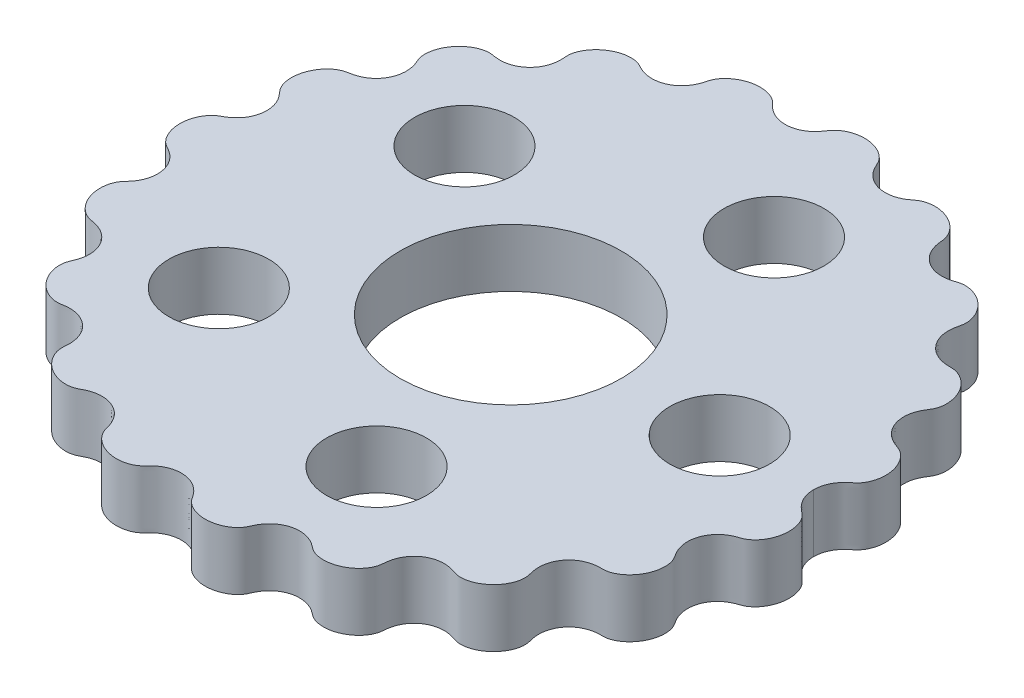
SolidWorks part; units mm, degrees
ref_plane "Front Plane" through (0, 0, 0) normal (0, 0, 1) x (1, 0, 0)
ref_plane "Top Plane" through (0, 0, 0) normal (0, 1, 0) x (1, 0, 0)
ref_plane "Right Plane" through (0, 0, 0) normal (1, 0, 0) x (0, 0, -1)
sketch "Sketch1" plane through (0, 0, 0) normal (0, 1, 0) x (1, 0, 0)
  line L0 (-28.5, 0) -> (26.1, 0) construction
  line L1 (0, 0) -> (-1.2, 0) construction
  line L2 (-1.2, -26.2965) -> (-1.2, 26.2965) construction
  line L3 (0, -27.4748) -> (0, 27.4748) construction
  line L4 (18, 0) -> (16.8, 0)
  line L5 (-1.2, 0) -> (-2.4, 0)
  circle A6 centre (0, 0) radius 9.525
  circle A7 centre (0, 0) radius 18
  circle A8 centre (18, 0) radius 4.3
  circle A9 centre (5.5623, -17.119) radius 4.3
  circle A10 centre (-14.5623, -10.5801) radius 4.3
  circle A11 centre (-14.5623, 10.5801) radius 4.3
  circle A12 centre (5.5623, 17.119) radius 4.3
  circle A13 centre (-1.2, 0) radius 30
  circle A14 centre (28.8, 0) radius 2.5
  circle A15 centre (27.3317, -9.2705) radius 2.5
  circle A16 centre (23.0705, -17.6336) radius 2.5
  circle A17 centre (16.4336, -24.2705) radius 2.5
  circle A18 centre (8.0705, -28.5317) radius 2.5
  circle A19 centre (-1.2, -30) radius 2.5
  circle A20 centre (-10.4705, -28.5317) radius 2.5
  circle A21 centre (-18.8336, -24.2705) radius 2.5
  circle A22 centre (-25.4705, -17.6336) radius 2.5
  circle A23 centre (-29.7317, -9.2705) radius 2.5
  circle A24 centre (-31.2, 0) radius 2.5
  circle A25 centre (-29.7317, 9.2705) radius 2.5
  circle A26 centre (-25.4705, 17.6336) radius 2.5
  circle A27 centre (-18.8336, 24.2705) radius 2.5
  circle A28 centre (-10.4705, 28.5317) radius 2.5
  circle A29 centre (-1.2, 30) radius 2.5
  circle A30 centre (8.0705, 28.5317) radius 2.5
  circle A31 centre (16.4336, 24.2705) radius 2.5
  circle A32 centre (23.0705, 17.6336) radius 2.5
  circle A33 centre (27.3317, 9.2705) radius 2.5
  circle A34 centre (-2.4, 0) radius 9.525
  circle A35 centre (-2.4, 0) radius 18
  circle A36 centre (15.6, 0) radius 4
  circle A37 centre (3.1623, -17.119) radius 4
  circle A38 centre (-16.9623, -10.5801) radius 4
  circle A39 centre (-16.9623, 10.5801) radius 4
  circle A40 centre (3.1623, 17.119) radius 4
  spline S0 degree 4 poles (26.9104, 6.6012) (26.9742, 6.5637) (27.0975, 6.4823) (27.3266, 6.2942) (27.6183, 5.9575) (27.8831, 5.5093) (28.0722, 4.9735) (28.1608, 4.4391) (28.1609, 3.9238) (28.093, 3.5007) (27.9838, 3.1507) (27.8591, 2.8784) (27.741, 2.6778) (27.605, 2.4959) (27.4503, 2.337) (27.2759, 2.2009) (27.1019, 2.0648) (26.9367, 1.9177) (26.7821, 1.7596) (26.65, 1.601) (26.5385, 1.4453) (26.4457, 1.295) (26.3692, 1.1524) (26.3017, 1.0053) (26.2435, 0.8544) (26.1947, 0.7002) (26.1557, 0.5423) (26.1271, 0.3877) (26.1084, 0.2314) (26.0989, 0.0495) (26.0994, -0.0671) (26.1108, -0.2691) (26.1342, -0.4315) (26.1693, -0.6042) (26.2157, -0.7717) (26.2733, -0.9361) (26.3418, -1.0961) (26.4279, -1.2656) (26.5348, -1.4419) (26.6997, -1.6703) (26.9014, -1.8899) (27.1248, -2.087) (27.3628, -2.2652) (27.5417, -2.4229) (27.6968, -2.6125) (27.831, -2.8239) (27.9427, -3.0552) (28.032, -3.3021) (28.1133, -3.6202) (28.1642, -4.0114) (28.1582, -4.4659) (28.0687, -4.972) (27.9224, -5.3919) (27.7522, -5.7264) (27.5792, -5.9861) (27.4226, -6.1811) (27.2087, -6.3966) (26.9704, -6.5815) (26.7043, -6.7144) (26.4261, -6.8021) (26.2084, -6.8853) (25.996, -6.9818) (25.7924, -7.0957) (25.5065, -7.2884) (25.1668, -7.5959) (24.8233, -8.0656) (24.5731, -8.7228) (24.5132, -9.3741) (24.5959, -9.9089) (24.7329, -10.3062) (24.8635, -10.5783) (24.9836, -10.7878) (25.1181, -10.988) (25.2439, -11.1944) (25.336, -11.4251) (25.3995, -11.6707) (25.4343, -11.9282) (25.442, -12.1937) (25.4188, -12.5249) (25.3424, -12.9166) (25.1912, -13.3478) (24.9449, -13.7987) (24.6361, -14.1974) (24.3194, -14.493) (24.0146, -14.7042) (23.7442, -14.8441) (23.522, -14.9308) (23.2952, -14.9909) (23.0662, -15.0181) (22.8362, -15.0154) (22.6065, -15.0188) (22.3771, -15.0374) (22.15, -15.0735) (21.9017, -15.1343) (21.6364, -15.2275) (21.2852, -15.3974) (20.867, -15.6962) (20.4577, -16.1544) (20.1676, -16.7441) (20.0407, -17.3441) (20.0443, -17.8376) (20.1013, -18.2083) (20.1783, -18.5102) (20.2374, -18.7529) (20.2542, -19.0071) (20.2367, -19.2645) (20.1753, -19.5877) (20.0454, -19.9662) (19.8257, -20.3791) (19.5033, -20.7922) (19.1257, -21.1406) (18.7061, -21.4192) (18.3126, -21.5978) (17.9573, -21.7007) (17.6591, -21.7472) (17.425, -21.7593) (17.197, -21.746) (16.9781, -21.7045) (16.7675, -21.6331) (16.5576, -21.5612) (16.3432, -21.5027) (16.1253, -21.4593) (15.7965, -21.4204) (15.3549, -21.428) (14.789, -21.5503) (14.1546, -21.8806) (13.6662, -22.3459) (13.3364, -22.8823) (13.1735, -23.3537) (13.1046, -23.717) (13.0767, -24.0228) (13.0578, -24.2682) (12.9987, -24.5141) (12.9032, -24.7542) (12.7442, -25.0453) (12.499, -25.369) (12.1557, -25.6963) (11.7049, -25.9946) (11.2116, -26.2122) (10.69, -26.3437) (10.2213, -26.3776) (9.8206, -26.3426) (9.499, -26.2667) (9.2556, -26.1771) (9.0298, -26.0566) (8.8316, -25.9026) (8.5839, -25.7111) (8.2645, -25.511) (7.8101, -25.3123) (7.2055, -25.1928) (6.5502, -25.2287) (5.9713, -25.4243) (5.5369, -25.6878) (5.2457, -25.9387) (5.0554, -26.1438) (4.8999, -26.3482) (4.7746, -26.5455) (4.6646, -26.7519) (4.569, -26.9649) (4.4763, -27.1796) (4.3535, -27.3793) (4.2033, -27.5619) (4.0321, -27.728) (3.7953, -27.9145) (3.4825, -28.1028) (3.0896, -28.2688) (2.605, -28.3883) (2.0954, -28.4312) (1.5735, -28.39) (1.1195, -28.2728) (0.7516, -28.1124) (0.4728, -27.9399) (0.2735, -27.7809) (0.1002, -27.6012) (-0.0369, -27.4007) (-0.1676, -27.1967) (-0.3131, -27.0024) (-0.5125, -26.7738) (-0.8252, -26.4899) (-1.2868, -26.2024) (-1.9065, -26.0034) (-2.5994, -25.9754) (-3.1568, -26.101) (-3.5653, -26.2832) (-3.8534, -26.4638) (-4.0409, -26.6046) (-4.2161, -26.7602) (-4.3804, -26.9272) (-4.5356, -27.1027) (-4.708, -27.2621) (-4.9066, -27.3955) (-5.1223, -27.5066) (-5.3531, -27.5948) (-5.5951, -27.6608) (-5.9041, -27.715) (-6.2804, -27.7366) (-6.7242, -27.7014) (-7.2225, -27.58) (-7.6392, -27.4035) (-7.9745, -27.2016) (-8.2316, -27.0015) (-8.4208, -26.8224) (-8.5884, -26.628) (-8.73, -26.4192) (-8.8438, -26.1979) (-8.9181, -25.9651) (-8.9731, -25.7277) (-9.0439, -25.4943) (-9.1531, -25.2096) (-9.3068, -24.9159) (-9.5135, -24.6237) (-9.8398, -24.2849) (-10.2644, -23.9778) (-10.8297, -23.7381) (-11.4105, -23.6609) (-11.8763, -23.6964) (-12.2188, -23.7735) (-12.4447, -23.8451) (-12.6638, -23.9353) (-12.8761, -24.0403) (-13.082, -24.1572) (-13.2986, -24.2543) (-13.5339, -24.3178) (-13.7805, -24.3538) (-14.0358, -24.3616) (-14.2964, -24.3431) (-14.6185, -24.2887) (-14.9949, -24.1775) (-15.4086, -23.9883) (-15.8372, -23.7006) (-16.1649, -23.3939) (-16.4043, -23.0978) (-16.5733, -22.8298) (-16.6877, -22.6036) (-16.7767, -22.3723) (-16.8377, -22.1385) (-16.8702, -21.9045) (-16.8664, -21.6745) (-16.8432, -21.4462) (-16.8326, -21.2169) (-16.8373, -20.9873) (-16.8603, -20.7588) (-16.9233, -20.4192) (-17.0718, -19.9806) (-17.369, -19.4772) (-17.8749, -18.9885) (-18.448, -18.6772) (-19.0275, -18.5257) (-19.5101, -18.5038) (-19.8766, -18.5383) (-20.1776, -18.5934) (-20.4214, -18.6224) (-20.6712, -18.6091) (-20.9209, -18.565) (-21.1679, -18.4906) (-21.4096, -18.39) (-21.6982, -18.2354) (-22.0201, -18.0093) (-22.351, -17.6983) (-22.6637, -17.2907) (-22.9048, -16.8434) (-23.0478, -16.4273) (-23.1163, -16.0571) (-23.132, -15.7508) (-23.1187, -15.5137) (-23.0797, -15.2858) (-23.0107, -15.072) (-22.918, -14.8679) (-22.8318, -14.6612) (-22.759, -14.4492) (-22.7023, -14.2323) (-22.658, -13.9823) (-22.6359, -13.6994) (-22.6507, -13.3001) (-22.7619, -12.7838) (-23.0293, -12.2149) (-23.4676, -11.712) (-23.9234, -11.3981) (-24.3155, -11.223) (-24.6094, -11.1314) (-24.8495, -11.076) (-25.0926, -11.0387) (-25.3345, -10.9908) (-25.5693, -10.9005) (-25.7937, -10.7797) (-26.006, -10.6307) (-26.2044, -10.4578) (-26.4303, -10.2184) (-26.6648, -9.8998) (-26.879, -9.4996) (-27.0444, -9.0157) (-27.13, -8.5201) (-27.1345, -8.0871) (-27.0849, -7.7198) (-27.006, -7.4259) (-26.9204, -7.2033) (-26.8122, -6.9952) (-26.6786, -6.8073) (-26.5213, -6.6394) (-26.3676, -6.4686) (-26.2255, -6.2877) (-26.0974, -6.0966) (-25.9747, -5.8762) (-25.8647, -5.6245) (-25.7524, -5.2647) (-25.6818, -4.7626) (-25.731, -4.1469) (-25.9619, -3.524) (-26.3213, -3.0106) (-26.6902, -2.673) (-27.001, -2.4627) (-27.2749, -2.314) (-27.4942, -2.1942) (-27.6938, -2.0358) (-27.8724, -1.8494) (-28.0299, -1.6395) (-28.1658, -1.4106) (-28.2784, -1.1691) (-28.3569, -0.9499) (-28.4099, -0.7574) (-28.4448, -0.5945) (-28.4671, -0.4646) (-28.4838, -0.3341) (-28.4949, -0.1942) (-28.5004, -0.0525) (-28.5005, 0.0456) (-28.4955, 0.1802) (-28.4857, 0.3127) (-28.4674, 0.4669) (-28.4356, 0.6491) (-28.3841, 0.8627) (-28.3055, 1.0987) (-28.2068, 1.3282) (-28.0876, 1.5473) (-27.9509, 1.7495) (-27.7973, 1.9316) (-27.6281, 2.0918) (-27.4431, 2.2241) (-27.2427, 2.3305) (-27.0445, 2.4404) (-26.8537, 2.5632) (-26.6725, 2.6998) (-26.4853, 2.8663) (-26.2987, 3.0673) (-26.073, 3.3712) (-25.8526, 3.7999) (-25.7033, 4.3429) (-25.6908, 4.9349) (-25.7972, 5.4631) (-25.983, 5.9142) (-26.1842, 6.2409) (-26.3898, 6.4964) (-26.5384, 6.6564) (-26.611, 6.7378) (-26.647, 6.7788) knots 0 0 0 0 0 0.002514 0.005029 0.010058 0.015086 0.020115 0.024264 0.028413 0.032562 0.034636 0.03671 0.038591 0.040472 0.042353 0.044234 0.046115 0.047995 0.049876 0.051757 0.053134 0.05451 0.055887 0.057263 0.05864 0.060016 0.061393 0.06277 0.064064 0.065358 0.066839 0.06832 0.069801 0.071282 0.072763 0.074244 0.075725 0.077206 0.079231 0.081256 0.085305 0.087329 0.089354 0.091379 0.093403 0.095635 0.097867 0.100099 0.102331 0.106795 0.111259 0.115506 0.119752 0.121875 0.123998 0.126122 0.128245 0.132212 0.134196 0.13618 0.138163 0.140147 0.142131 0.144114 0.149889 0.155664 0.161717 0.167769 0.171876 0.173929 0.175982 0.178036 0.180089 0.182142 0.184196 0.186453 0.18871 0.190968 0.193225 0.19774 0.202255 0.20645 0.210645 0.21484 0.216937 0.219035 0.220991 0.222947 0.224903 0.226859 0.228815 0.230771 0.232727 0.234683 0.237505 0.240328 0.245974 0.252074 0.258174 0.262418 0.266663 0.268785 0.270907 0.27303 0.275152 0.277414 0.279676 0.284201 0.288725 0.29325 0.297435 0.301619 0.305804 0.307896 0.309989 0.311878 0.313768 0.315658 0.317547 0.319437 0.321327 0.323216 0.325106 0.330698 0.336289 0.342722 0.349154 0.353338 0.357522 0.359614 0.361706 0.363798 0.365889 0.368184 0.370478 0.375067 0.379656 0.384245 0.388791 0.393338 0.397884 0.400157 0.40243 0.404563 0.406695 0.408827 0.41096 0.415225 0.41949 0.425619 0.431749 0.437282 0.440049 0.442815 0.444803 0.446791 0.448779 0.450767 0.452755 0.454743 0.456731 0.458718 0.460784 0.462849 0.466979 0.47111 0.47524 0.479777 0.484314 0.488851 0.491119 0.493388 0.495451 0.497514 0.499578 0.501641 0.503704 0.505768 0.509894 0.515977 0.52206 0.527644 0.533228 0.535221 0.537214 0.539208 0.541201 0.543194 0.545187 0.54718 0.549173 0.551306 0.553439 0.555572 0.557704 0.56197 0.566236 0.570665 0.575094 0.577308 0.579523 0.581737 0.583952 0.586026 0.5881 0.590174 0.592248 0.594322 0.596397 0.600545 0.6035 0.606456 0.612367 0.618261 0.624154 0.626169 0.628184 0.630198 0.632213 0.634228 0.636243 0.638257 0.640272 0.642493 0.644714 0.646935 0.649156 0.653597 0.658039 0.662348 0.666657 0.668812 0.670967 0.673121 0.675276 0.677229 0.679181 0.681134 0.683087 0.68504 0.686993 0.688946 0.690899 0.696786 0.702673 0.708614 0.714556 0.718724 0.722892 0.724976 0.72706 0.729144 0.731229 0.733454 0.73568 0.737906 0.740131 0.744583 0.749034 0.753293 0.757552 0.76181 0.76394 0.766069 0.767975 0.769882 0.771788 0.773694 0.775601 0.777507 0.779413 0.78132 0.784235 0.787151 0.792981 0.799177 0.805373 0.809561 0.811656 0.81375 0.815844 0.817939 0.820033 0.822127 0.824365 0.826603 0.828841 0.831079 0.835554 0.84003 0.844223 0.848415 0.852608 0.854705 0.856801 0.858757 0.860713 0.862669 0.864625 0.866581 0.868537 0.870493 0.87245 0.875161 0.877872 0.883295 0.889615 0.895936 0.900182 0.904428 0.906551 0.908674 0.910797 0.912919 0.915183 0.917446 0.919709 0.921972 0.924235 0.925367 0.926498 0.92763 0.928762 0.929893 0.931025 0.932085 0.933146 0.934206 0.935267 0.937388 0.939509 0.94163 0.943751 0.945872 0.947993 0.949922 0.951852 0.953781 0.95571 0.95764 0.959569 0.961498 0.963428 0.966159 0.968891 0.974355 0.979745 0.985135 0.988851 0.992568 0.996284 0.998142 1 1 1 1 1 construction
  spline S1 degree 4 poles (26.1, 0) (26.1, -0.0377) (26.102, -0.1127) (26.1108, -0.2691) (26.1342, -0.4315) (26.1693, -0.6042) (26.2157, -0.7717) (26.2733, -0.9361) (26.3418, -1.0961) (26.4279, -1.2656) (26.5348, -1.4419) (26.6997, -1.6703) (26.9014, -1.8899) (27.1248, -2.087) (27.3628, -2.2652) (27.5417, -2.4229) (27.6968, -2.6125) (27.831, -2.8239) (27.9427, -3.0552) (28.032, -3.3021) (28.1133, -3.6202) (28.1642, -4.0114) (28.1582, -4.4659) (28.0687, -4.972) (27.9224, -5.3919) (27.7522, -5.7264) (27.5792, -5.9861) (27.4226, -6.1811) (27.2087, -6.3966) (26.9704, -6.5815) (26.7043, -6.7144) (26.4261, -6.8021) (26.2084, -6.8853) (25.996, -6.9818) (25.7924, -7.0957) (25.5065, -7.2884) (25.1668, -7.5959) (24.8233, -8.0656) (24.5731, -8.7228) (24.5132, -9.3741) (24.5959, -9.9089) (24.7329, -10.3062) (24.8635, -10.5783) (24.9836, -10.7878) (25.1181, -10.988) (25.2439, -11.1944) (25.336, -11.4251) (25.3995, -11.6707) (25.4343, -11.9282) (25.442, -12.1937) (25.4188, -12.5249) (25.3424, -12.9166) (25.1912, -13.3478) (24.9449, -13.7987) (24.6361, -14.1974) (24.3194, -14.493) (24.0146, -14.7042) (23.7442, -14.8441) (23.522, -14.9308) (23.2952, -14.9909) (23.0662, -15.0181) (22.8362, -15.0154) (22.6065, -15.0188) (22.3771, -15.0374) (22.15, -15.0735) (21.9017, -15.1343) (21.6364, -15.2275) (21.2852, -15.3974) (20.867, -15.6962) (20.4577, -16.1544) (20.1676, -16.7441) (20.0407, -17.3441) (20.0443, -17.8376) (20.1013, -18.2083) (20.1783, -18.5102) (20.2374, -18.7529) (20.2542, -19.0071) (20.2367, -19.2645) (20.1753, -19.5877) (20.0454, -19.9662) (19.8257, -20.3791) (19.5033, -20.7922) (19.1257, -21.1406) (18.7061, -21.4192) (18.3126, -21.5978) (17.9573, -21.7007) (17.6591, -21.7472) (17.425, -21.7593) (17.197, -21.746) (16.9781, -21.7045) (16.7675, -21.6331) (16.5576, -21.5612) (16.3432, -21.5027) (16.1253, -21.4593) (15.7965, -21.4204) (15.3549, -21.428) (14.789, -21.5503) (14.1546, -21.8806) (13.6662, -22.3459) (13.3364, -22.8823) (13.1735, -23.3537) (13.1046, -23.717) (13.0767, -24.0228) (13.0578, -24.2682) (12.9987, -24.5141) (12.9032, -24.7542) (12.7442, -25.0453) (12.499, -25.369) (12.1557, -25.6963) (11.7049, -25.9946) (11.2116, -26.2122) (10.69, -26.3437) (10.2213, -26.3776) (9.8206, -26.3426) (9.499, -26.2667) (9.2556, -26.1771) (9.0298, -26.0566) (8.8316, -25.9026) (8.5839, -25.7111) (8.2645, -25.511) (7.8101, -25.3123) (7.2055, -25.1928) (6.5502, -25.2287) (5.9713, -25.4243) (5.5369, -25.6878) (5.2457, -25.9387) (5.0554, -26.1438) (4.8999, -26.3482) (4.7746, -26.5455) (4.6646, -26.7519) (4.569, -26.9649) (4.4763, -27.1796) (4.3535, -27.3793) (4.2033, -27.5619) (4.0321, -27.728) (3.7953, -27.9145) (3.4825, -28.1028) (3.0896, -28.2688) (2.605, -28.3883) (2.0954, -28.4312) (1.5735, -28.39) (1.1195, -28.2728) (0.7516, -28.1124) (0.4728, -27.9399) (0.2735, -27.7809) (0.1002, -27.6012) (-0.0369, -27.4007) (-0.1676, -27.1967) (-0.3131, -27.0024) (-0.5125, -26.7738) (-0.8252, -26.4899) (-1.2868, -26.2024) (-1.9065, -26.0034) (-2.5994, -25.9754) (-3.1568, -26.101) (-3.5653, -26.2832) (-3.8534, -26.4638) (-4.0409, -26.6046) (-4.2161, -26.7602) (-4.3804, -26.9272) (-4.5356, -27.1027) (-4.708, -27.2621) (-4.9066, -27.3955) (-5.1223, -27.5066) (-5.3531, -27.5948) (-5.5951, -27.6608) (-5.9041, -27.715) (-6.2804, -27.7366) (-6.7242, -27.7014) (-7.2225, -27.58) (-7.6392, -27.4035) (-7.9745, -27.2016) (-8.2316, -27.0015) (-8.4208, -26.8224) (-8.5884, -26.628) (-8.73, -26.4192) (-8.8438, -26.1979) (-8.9181, -25.9651) (-8.9731, -25.7277) (-9.0439, -25.4943) (-9.1531, -25.2096) (-9.3068, -24.9159) (-9.5135, -24.6237) (-9.8398, -24.2849) (-10.2644, -23.9778) (-10.8297, -23.7381) (-11.4105, -23.6609) (-11.8763, -23.6964) (-12.2188, -23.7735) (-12.4447, -23.8451) (-12.6638, -23.9353) (-12.8761, -24.0403) (-13.082, -24.1572) (-13.2986, -24.2543) (-13.5339, -24.3178) (-13.7805, -24.3538) (-14.0358, -24.3616) (-14.2964, -24.3431) (-14.6185, -24.2887) (-14.9949, -24.1775) (-15.4086, -23.9883) (-15.8372, -23.7006) (-16.1649, -23.3939) (-16.4043, -23.0978) (-16.5733, -22.8298) (-16.6877, -22.6036) (-16.7767, -22.3723) (-16.8377, -22.1385) (-16.8702, -21.9045) (-16.8664, -21.6745) (-16.8432, -21.4462) (-16.8326, -21.2169) (-16.8373, -20.9873) (-16.8603, -20.7588) (-16.9233, -20.4192) (-17.0718, -19.9806) (-17.369, -19.4772) (-17.8749, -18.9885) (-18.448, -18.6772) (-19.0275, -18.5257) (-19.5101, -18.5038) (-19.8766, -18.5383) (-20.1776, -18.5934) (-20.4214, -18.6224) (-20.6712, -18.6091) (-20.9209, -18.565) (-21.1679, -18.4906) (-21.4096, -18.39) (-21.6982, -18.2354) (-22.0201, -18.0093) (-22.351, -17.6983) (-22.6637, -17.2907) (-22.9048, -16.8434) (-23.0478, -16.4273) (-23.1163, -16.0571) (-23.132, -15.7508) (-23.1187, -15.5137) (-23.0797, -15.2858) (-23.0107, -15.072) (-22.918, -14.8679) (-22.8318, -14.6612) (-22.759, -14.4492) (-22.7023, -14.2323) (-22.658, -13.9823) (-22.6359, -13.6994) (-22.6507, -13.3001) (-22.7619, -12.7838) (-23.0293, -12.2149) (-23.4676, -11.712) (-23.9234, -11.3981) (-24.3155, -11.223) (-24.6094, -11.1314) (-24.8495, -11.076) (-25.0926, -11.0387) (-25.3345, -10.9908) (-25.5693, -10.9005) (-25.7937, -10.7797) (-26.006, -10.6307) (-26.2044, -10.4578) (-26.4303, -10.2184) (-26.6648, -9.8998) (-26.879, -9.4996) (-27.0444, -9.0157) (-27.13, -8.5201) (-27.1345, -8.0871) (-27.0849, -7.7198) (-27.006, -7.4259) (-26.9204, -7.2033) (-26.8122, -6.9952) (-26.6786, -6.8073) (-26.5213, -6.6394) (-26.3676, -6.4686) (-26.2255, -6.2877) (-26.0974, -6.0966) (-25.9747, -5.8762) (-25.8647, -5.6245) (-25.7524, -5.2647) (-25.6818, -4.7626) (-25.731, -4.1469) (-25.9619, -3.524) (-26.3213, -3.0106) (-26.6902, -2.673) (-27.001, -2.4627) (-27.2749, -2.314) (-27.4942, -2.1942) (-27.6938, -2.0358) (-27.8724, -1.8494) (-28.0299, -1.6395) (-28.1658, -1.4106) (-28.2784, -1.1691) (-28.3569, -0.9499) (-28.4099, -0.7574) (-28.4448, -0.5945) (-28.4671, -0.4646) (-28.4838, -0.3341) (-28.4949, -0.1942) (-28.4991, -0.0862) (-28.5, -0.0288) (-28.5, 0) knots 0.065358 0.065358 0.065358 0.065358 0.065358 0.066839 0.06832 0.069801 0.071282 0.072763 0.074244 0.075725 0.077206 0.079231 0.081256 0.085305 0.087329 0.089354 0.091379 0.093403 0.095635 0.097867 0.100099 0.102331 0.106795 0.111259 0.115506 0.119752 0.121875 0.123998 0.126122 0.128245 0.132212 0.134196 0.13618 0.138163 0.140147 0.142131 0.144114 0.149889 0.155664 0.161717 0.167769 0.171876 0.173929 0.175982 0.178036 0.180089 0.182142 0.184196 0.186453 0.18871 0.190968 0.193225 0.19774 0.202255 0.20645 0.210645 0.21484 0.216937 0.219035 0.220991 0.222947 0.224903 0.226859 0.228815 0.230771 0.232727 0.234683 0.237505 0.240328 0.245974 0.252074 0.258174 0.262418 0.266663 0.268785 0.270907 0.27303 0.275152 0.277414 0.279676 0.284201 0.288725 0.29325 0.297435 0.301619 0.305804 0.307896 0.309989 0.311878 0.313768 0.315658 0.317547 0.319437 0.321327 0.323216 0.325106 0.330698 0.336289 0.342722 0.349154 0.353338 0.357522 0.359614 0.361706 0.363798 0.365889 0.368184 0.370478 0.375067 0.379656 0.384245 0.388791 0.393338 0.397884 0.400157 0.40243 0.404563 0.406695 0.408827 0.41096 0.415225 0.41949 0.425619 0.431749 0.437282 0.440049 0.442815 0.444803 0.446791 0.448779 0.450767 0.452755 0.454743 0.456731 0.458718 0.460784 0.462849 0.466979 0.47111 0.47524 0.479777 0.484314 0.488851 0.491119 0.493388 0.495451 0.497514 0.499578 0.501641 0.503704 0.505768 0.509894 0.515977 0.52206 0.527644 0.533228 0.535221 0.537214 0.539208 0.541201 0.543194 0.545187 0.54718 0.549173 0.551306 0.553439 0.555572 0.557704 0.56197 0.566236 0.570665 0.575094 0.577308 0.579523 0.581737 0.583952 0.586026 0.5881 0.590174 0.592248 0.594322 0.596397 0.600545 0.6035 0.606456 0.612367 0.618261 0.624154 0.626169 0.628184 0.630198 0.632213 0.634228 0.636243 0.638257 0.640272 0.642493 0.644714 0.646935 0.649156 0.653597 0.658039 0.662348 0.666657 0.668812 0.670967 0.673121 0.675276 0.677229 0.679181 0.681134 0.683087 0.68504 0.686993 0.688946 0.690899 0.696786 0.702673 0.708614 0.714556 0.718724 0.722892 0.724976 0.72706 0.729144 0.731229 0.733454 0.73568 0.737906 0.740131 0.744583 0.749034 0.753293 0.757552 0.76181 0.76394 0.766069 0.767975 0.769882 0.771788 0.773694 0.775601 0.777507 0.779413 0.78132 0.784235 0.787151 0.792981 0.799177 0.805373 0.809561 0.811656 0.81375 0.815844 0.817939 0.820033 0.822127 0.824365 0.826603 0.828841 0.831079 0.835554 0.84003 0.844223 0.848415 0.852608 0.854705 0.856801 0.858757 0.860713 0.862669 0.864625 0.866581 0.868537 0.870493 0.87245 0.875161 0.877872 0.883295 0.889615 0.895936 0.900182 0.904428 0.906551 0.908674 0.910797 0.912919 0.915183 0.917446 0.919709 0.921972 0.924235 0.925367 0.926498 0.92763 0.928762 0.929893 0.931025 0.931025 0.931025 0.931025 0.931025
  spline S2 degree 4 poles (26.1, 0) (26.1, 0.0376) (26.102, 0.1124) (26.1108, 0.2685) (26.1342, 0.4303) (26.1693, 0.6027) (26.2157, 0.7697) (26.2733, 0.9336) (26.3417, 1.0932) (26.4279, 1.2622) (26.5346, 1.438) (26.6647, 1.6175) (26.8202, 1.7972) (26.9901, 1.9633) (27.1709, 2.1172) (27.3596, 2.2614) (27.5347, 2.4225) (27.6873, 2.6133) (27.8194, 2.8254) (27.9294, 3.0568) (28.0174, 3.3035) (28.0973, 3.6212) (28.1472, 4.0116) (28.1407, 4.4663) (28.0507, 4.9735) (27.8829, 5.455) (27.6715, 5.843) (27.4436, 6.1449) (27.2267, 6.3648) (27.0409, 6.5166) (26.8436, 6.6432) (26.6359, 6.7382) (26.4199, 6.8111) (26.2069, 6.8919) (25.9995, 6.9866) (25.7999, 7.097) (25.5146, 7.2869) (25.172, 7.593) (24.8251, 8.0632) (24.573, 8.723) (24.5135, 9.3751) (24.5967, 9.9085) (24.7339, 10.3046) (24.8642, 10.5762) (24.9838, 10.7853) (25.1166, 10.986) (25.2378, 11.1945) (25.3267, 11.4258) (25.3878, 11.6713) (25.4209, 11.9285) (25.4273, 12.1933) (25.4029, 12.5237) (25.3257, 12.9142) (25.174, 13.3453) (24.9269, 13.7973) (24.6164, 14.1978) (24.297, 14.4955) (23.9896, 14.7081) (23.7185, 14.8479) (23.4979, 14.934) (23.2747, 14.9937) (23.0513, 15.0227) (22.8265, 15.0238) (22.6021, 15.0278) (22.378, 15.046) (22.1559, 15.0804) (21.8286, 15.1585) (21.4093, 15.3223) (20.9247, 15.6352) (20.4568, 16.1578) (20.1669, 16.7485) (20.041, 17.3471) (20.0453, 17.8394) (20.1023, 18.2092) (20.1778, 18.5107) (20.2318, 18.7541) (20.2449, 19.0078) (20.2252, 19.2644) (20.1746, 19.5212) (20.0962, 19.7748) (19.9675, 20.0808) (19.7692, 20.427) (19.4884, 20.786) (19.1123, 21.133) (18.6951, 21.411) (18.3044, 21.5899) (17.9516, 21.6944) (17.5971, 21.7522) (17.3027, 21.7613) (17.0135, 21.7242) (16.7419, 21.6352) (16.5255, 21.5634) (16.3045, 21.5051) (16.08, 21.4631) (15.8308, 21.4372) (15.5583, 21.4348) (15.1861, 21.4722) (14.6961, 21.6037) (14.1458, 21.8923) (13.6634, 22.3528) (13.3351, 22.8883) (13.1733, 23.3588) (13.1047, 23.7212) (13.0759, 24.0263) (13.0525, 24.2707) (12.9895, 24.515) (12.8921, 24.7535) (12.7313, 25.0427) (12.4854, 25.3645) (12.1419, 25.6899) (11.6909, 25.9876) (11.1964, 26.2054) (10.6723, 26.3373) (10.2003, 26.3711) (9.7968, 26.3356) (9.4748, 26.2593) (9.233, 26.1706) (9.01, 26.0529) (8.8137, 25.9055) (8.5704, 25.7195) (8.2582, 25.5237) (7.8094, 25.325) (7.2073, 25.202) (6.5461, 25.2353) (5.8772, 25.4622) (5.3986, 25.786) (5.085, 26.1055) (4.8853, 26.3742) (4.7666, 26.5637) (4.6617, 26.7612) (4.5693, 26.9645) (4.4773, 27.1684) (4.3594, 27.359) (4.2144, 27.5373) (4.0466, 27.7027) (3.8098, 27.8925) (3.4925, 28.0862) (3.093, 28.2569) (2.6024, 28.3789) (2.0891, 28.4226) (1.566, 28.382) (1.1127, 28.2662) (0.7451, 28.1078) (0.4658, 27.9376) (0.2655, 27.7808) (0.0903, 27.6039) (-0.0506, 27.4068) (-0.1822, 27.204) (-0.3275, 27.0102) (-0.5264, 26.7821) (-0.838, 26.4986) (-1.2981, 26.2111) (-1.9184, 26.0114) (-2.6145, 25.984) (-3.1735, 26.1125) (-3.582, 26.2979) (-3.8673, 26.4791) (-4.0499, 26.6174) (-4.2212, 26.7695) (-4.3819, 26.9324) (-4.5359, 27.1018) (-4.7063, 27.2554) (-4.9021, 27.3863) (-5.1165, 27.4966) (-5.3472, 27.5851) (-5.5911, 27.6519) (-5.9024, 27.7067) (-6.2817, 27.7289) (-6.73, 27.6934) (-7.2343, 27.5702) (-7.6563, 27.3905) (-7.9967, 27.1843) (-8.2563, 26.9795) (-8.4483, 26.7967) (-8.6511, 26.5554) (-8.817, 26.2938) (-8.9134, 26.0392) (-8.9701, 25.8124) (-9.0327, 25.5873) (-9.1257, 25.31) (-9.3159, 24.91) (-9.6747, 24.4361) (-10.1835, 24.0258) (-10.8362, 23.7471) (-11.4204, 23.6699) (-11.885, 23.7058) (-12.2267, 23.7831) (-12.452, 23.8548) (-12.6708, 23.9446) (-12.8827, 24.0491) (-13.0896, 24.1633) (-13.3076, 24.2559) (-13.543, 24.3166) (-13.7894, 24.3504) (-14.0442, 24.3567) (-14.3041, 24.337) (-14.6252, 24.2816) (-15.0005, 24.1698) (-15.413, 23.9806) (-15.8407, 23.6936) (-16.2143, 23.3448) (-16.485, 22.9926) (-16.6692, 22.6601) (-16.7825, 22.3711) (-16.8455, 22.1383) (-16.8805, 21.9053) (-16.8813, 21.6757) (-16.8608, 21.4476) (-16.8506, 21.2188) (-16.8554, 20.9897) (-16.8782, 20.7616) (-16.9407, 20.4228) (-17.0884, 19.9851) (-17.3858, 19.4807) (-17.8945, 18.9905) (-18.4699, 18.6811) (-18.9904, 18.5487) (-19.4065, 18.5188) (-19.706, 18.5311) (-19.9442, 18.558) (-20.1802, 18.5992) (-20.4191, 18.6236) (-20.6652, 18.6099) (-20.9131, 18.5657) (-21.1602, 18.4916) (-21.4036, 18.3903) (-21.6943, 18.2349) (-22.0185, 18.0074) (-22.3518, 17.6944) (-22.6668, 17.2838) (-22.9095, 16.8332) (-23.0533, 16.4139) (-23.122, 16.0408) (-23.1375, 15.7333) (-23.1242, 15.4968) (-23.0858, 15.2707) (-23.0198, 15.0593) (-22.9309, 14.8568) (-22.847, 14.6525) (-22.7758, 14.4431) (-22.7201, 14.2291) (-22.6612, 13.8972) (-22.6444, 13.4427) (-22.7419, 12.8653) (-23.0456, 12.2192) (-23.4424, 11.7647) (-23.8363, 11.4753) (-24.161, 11.3062) (-24.3884, 11.2127) (-24.6231, 11.1398) (-24.8625, 11.0843) (-25.1048, 11.0455) (-25.3451, 10.9926) (-25.5781, 10.8996) (-25.8009, 10.7771) (-26.0117, 10.6271) (-26.2088, 10.4536) (-26.4333, 10.2139) (-26.6665, 9.8956) (-26.8796, 9.4961) (-27.0447, 9.0134) (-27.1306, 8.5189) (-27.1361, 8.0869) (-27.0881, 7.7202) (-27.0111, 7.4265) (-26.9274, 7.2037) (-26.8215, 6.9951) (-26.6914, 6.8052) (-26.5372, 6.635) (-26.3844, 6.4641) (-26.2428, 6.2834) (-26.1149, 6.0928) (-25.9923, 5.8728) (-25.8823, 5.6218) (-25.77, 5.2629) (-25.699, 4.7597) (-25.7493, 4.1408) (-25.9834, 3.518) (-26.345, 3.0082) (-26.7118, 2.6756) (-27.016, 2.4701) (-27.2831, 2.3232) (-27.4957, 2.2024) (-27.6915, 2.0453) (-27.8687, 1.86) (-28.0262, 1.6502) (-28.1632, 1.4198) (-28.2767, 1.1768) (-28.3557, 0.9562) (-28.4092, 0.7624) (-28.4443, 0.5985) (-28.4668, 0.4676) (-28.4836, 0.3363) (-28.4949, 0.1958) (-28.4991, 0.0868) (-28.5, 0.029) (-28.5, 0) knots 0.065429 0.065429 0.065429 0.065429 0.065429 0.066909 0.06839 0.06987 0.071351 0.072832 0.074312 0.075793 0.077274 0.079299 0.081323 0.083348 0.085373 0.087398 0.089423 0.091448 0.093473 0.095705 0.097936 0.100168 0.1024 0.106864 0.111328 0.115615 0.119903 0.124191 0.126335 0.128478 0.130422 0.132365 0.134309 0.136252 0.138195 0.140139 0.142082 0.144026 0.149879 0.155733 0.161783 0.167834 0.17194 0.173994 0.176047 0.1781 0.180154 0.182207 0.184261 0.186518 0.188775 0.191032 0.193289 0.197803 0.202317 0.206554 0.210791 0.215028 0.217147 0.219265 0.221181 0.223096 0.225012 0.226928 0.228843 0.230759 0.232675 0.23459 0.240315 0.24604 0.252138 0.258236 0.26248 0.266724 0.268846 0.270968 0.273091 0.275213 0.277474 0.279736 0.281998 0.28426 0.288783 0.293307 0.297478 0.30165 0.305822 0.307907 0.309993 0.313887 0.315834 0.317781 0.319728 0.321675 0.323622 0.325569 0.328265 0.330961 0.336353 0.342782 0.349211 0.353395 0.357579 0.35967 0.361762 0.363854 0.365946 0.36824 0.370534 0.375121 0.379709 0.384296 0.388885 0.393473 0.398062 0.400356 0.40265 0.404741 0.406832 0.408922 0.411013 0.415194 0.419375 0.425582 0.43179 0.437484 0.443178 0.445084 0.44699 0.448896 0.450802 0.452707 0.454613 0.456519 0.458425 0.460533 0.46264 0.466855 0.471071 0.475286 0.479822 0.484358 0.488895 0.491163 0.493431 0.495494 0.497557 0.499621 0.501684 0.503747 0.505811 0.509937 0.516018 0.522099 0.527761 0.533424 0.535376 0.537328 0.539281 0.541233 0.543185 0.545137 0.547089 0.549041 0.551195 0.55335 0.555504 0.557658 0.561967 0.566275 0.570786 0.575296 0.577551 0.579806 0.582061 0.584316 0.588304 0.590297 0.591294 0.592291 0.596278 0.600266 0.606335 0.612404 0.618295 0.624187 0.626202 0.628218 0.630233 0.632248 0.634263 0.636278 0.638293 0.640308 0.642529 0.64475 0.646971 0.649191 0.653633 0.658074 0.662384 0.666693 0.671002 0.673157 0.675311 0.677265 0.679218 0.681171 0.683124 0.685077 0.68703 0.688983 0.690936 0.696822 0.702707 0.708727 0.714747 0.718834 0.720878 0.722922 0.724965 0.727009 0.729053 0.731096 0.733342 0.735588 0.737834 0.74008 0.744572 0.749064 0.753364 0.757665 0.761965 0.764115 0.766265 0.76815 0.770035 0.771919 0.773804 0.775689 0.777574 0.779458 0.781343 0.787178 0.793013 0.799206 0.805399 0.807494 0.809588 0.811682 0.813777 0.815871 0.817965 0.82006 0.822154 0.824391 0.826629 0.828866 0.831104 0.835579 0.840053 0.844247 0.84844 0.852634 0.854731 0.856827 0.858784 0.86074 0.862697 0.864654 0.86661 0.868567 0.870523 0.87248 0.875191 0.877902 0.883324 0.889723 0.896121 0.900285 0.904449 0.906531 0.908613 0.910695 0.912776 0.91506 0.917343 0.919626 0.92191 0.924193 0.925335 0.926476 0.927618 0.92876 0.929901 0.931043 0.931043 0.931043 0.931043 0.931043
  spline S3 degree 4 poles (-28.5, 0) (-28.5, -0.0377) (-28.502, -0.1127) (-28.5108, -0.2691) (-28.5342, -0.4315) (-28.5693, -0.6042) (-28.6157, -0.7717) (-28.6733, -0.9361) (-28.7418, -1.0961) (-28.8279, -1.2656) (-28.9348, -1.4419) (-29.0997, -1.6703) (-29.3014, -1.8899) (-29.5248, -2.087) (-29.7628, -2.2652) (-29.9417, -2.4229) (-30.0968, -2.6125) (-30.231, -2.8239) (-30.3427, -3.0552) (-30.432, -3.3021) (-30.5133, -3.6202) (-30.5642, -4.0114) (-30.5582, -4.4659) (-30.4687, -4.972) (-30.3224, -5.3919) (-30.1522, -5.7264) (-29.9792, -5.9861) (-29.8226, -6.1811) (-29.6087, -6.3966) (-29.3704, -6.5815) (-29.1043, -6.7144) (-28.8261, -6.8021) (-28.6084, -6.8853) (-28.396, -6.9818) (-28.1924, -7.0957) (-27.9065, -7.2884) (-27.5668, -7.5959) (-27.2233, -8.0656) (-26.9731, -8.7228) (-26.9132, -9.3741) (-26.9959, -9.9089) (-27.1329, -10.3062) (-27.2635, -10.5783) (-27.3836, -10.7878) (-27.5181, -10.988) (-27.6439, -11.1944) (-27.736, -11.4251) (-27.7995, -11.6707) (-27.8343, -11.9282) (-27.842, -12.1937) (-27.8188, -12.5249) (-27.7424, -12.9166) (-27.5912, -13.3478) (-27.3449, -13.7987) (-27.0361, -14.1974) (-26.7194, -14.493) (-26.4146, -14.7042) (-26.1442, -14.8441) (-25.922, -14.9308) (-25.6952, -14.9909) (-25.4662, -15.0181) (-25.2362, -15.0154) (-25.0065, -15.0188) (-24.7771, -15.0374) (-24.55, -15.0735) (-24.3017, -15.1343) (-24.0364, -15.2275) (-23.6852, -15.3974) (-23.267, -15.6962) (-22.8577, -16.1544) (-22.5676, -16.7441) (-22.4407, -17.3441) (-22.4443, -17.8376) (-22.5013, -18.2083) (-22.5783, -18.5102) (-22.6374, -18.7529) (-22.6542, -19.0071) (-22.6367, -19.2645) (-22.5753, -19.5877) (-22.4454, -19.9662) (-22.2257, -20.3791) (-21.9033, -20.7922) (-21.5257, -21.1406) (-21.1061, -21.4192) (-20.7126, -21.5978) (-20.3573, -21.7007) (-20.0591, -21.7472) (-19.825, -21.7593) (-19.597, -21.746) (-19.3781, -21.7045) (-19.1675, -21.6331) (-18.9576, -21.5612) (-18.7432, -21.5027) (-18.5253, -21.4593) (-18.1965, -21.4204) (-17.7549, -21.428) (-17.189, -21.5503) (-16.5546, -21.8806) (-16.0662, -22.3459) (-15.7364, -22.8823) (-15.5735, -23.3537) (-15.5046, -23.717) (-15.4767, -24.0228) (-15.4578, -24.2682) (-15.3987, -24.5141) (-15.3032, -24.7542) (-15.1442, -25.0453) (-14.899, -25.369) (-14.5557, -25.6963) (-14.1049, -25.9946) (-13.6116, -26.2122) (-13.09, -26.3437) (-12.6213, -26.3776) (-12.2206, -26.3426) (-11.899, -26.2667) (-11.6556, -26.1771) (-11.4298, -26.0566) (-11.2316, -25.9026) (-10.9839, -25.7111) (-10.6645, -25.511) (-10.2101, -25.3123) (-9.6055, -25.1928) (-8.9502, -25.2287) (-8.3713, -25.4243) (-7.9369, -25.6878) (-7.6457, -25.9387) (-7.4554, -26.1438) (-7.2999, -26.3482) (-7.1746, -26.5455) (-7.0646, -26.7519) (-6.969, -26.9649) (-6.8763, -27.1796) (-6.7535, -27.3793) (-6.6033, -27.5619) (-6.4321, -27.728) (-6.1953, -27.9145) (-5.8825, -28.1028) (-5.4896, -28.2688) (-5.005, -28.3883) (-4.4954, -28.4312) (-3.9735, -28.39) (-3.5195, -28.2728) (-3.1516, -28.1124) (-2.8728, -27.9399) (-2.6735, -27.7809) (-2.5002, -27.6012) (-2.3631, -27.4007) (-2.2324, -27.1967) (-2.0869, -27.0024) (-1.8875, -26.7738) (-1.5748, -26.4899) (-1.1132, -26.2024) (-0.4935, -26.0034) (0.1994, -25.9754) (0.7568, -26.101) (1.1653, -26.2832) (1.4534, -26.4638) (1.6409, -26.6046) (1.8161, -26.7602) (1.9804, -26.9272) (2.1356, -27.1027) (2.308, -27.2621) (2.5066, -27.3955) (2.7223, -27.5066) (2.9531, -27.5948) (3.1951, -27.6608) (3.5041, -27.715) (3.8804, -27.7366) (4.3242, -27.7014) (4.8225, -27.58) (5.2392, -27.4035) (5.5745, -27.2016) (5.8316, -27.0015) (6.0208, -26.8224) (6.1884, -26.628) (6.33, -26.4192) (6.4438, -26.1979) (6.5181, -25.9651) (6.5731, -25.7277) (6.6439, -25.4943) (6.7531, -25.2096) (6.9068, -24.9159) (7.1135, -24.6237) (7.4398, -24.2849) (7.8644, -23.9778) (8.4297, -23.7381) (9.0105, -23.6609) (9.4763, -23.6964) (9.8188, -23.7735) (10.0447, -23.8451) (10.2638, -23.9353) (10.4761, -24.0403) (10.682, -24.1572) (10.8986, -24.2543) (11.1339, -24.3178) (11.3805, -24.3538) (11.6358, -24.3616) (11.8964, -24.3431) (12.2185, -24.2887) (12.5949, -24.1775) (13.0086, -23.9883) (13.4372, -23.7006) (13.7649, -23.3939) (14.0043, -23.0978) (14.1733, -22.8298) (14.2877, -22.6036) (14.3767, -22.3723) (14.4377, -22.1385) (14.4702, -21.9045) (14.4664, -21.6745) (14.4432, -21.4462) (14.4326, -21.2169) (14.4373, -20.9873) (14.4603, -20.7588) (14.5233, -20.4192) (14.6718, -19.9806) (14.969, -19.4772) (15.4749, -18.9885) (16.048, -18.6772) (16.6275, -18.5257) (17.1101, -18.5038) (17.4766, -18.5383) (17.7776, -18.5934) (18.0214, -18.6224) (18.2712, -18.6091) (18.5209, -18.565) (18.7679, -18.4906) (19.0096, -18.39) (19.2982, -18.2354) (19.6201, -18.0093) (19.951, -17.6983) (20.2637, -17.2907) (20.5048, -16.8434) (20.6478, -16.4273) (20.7163, -16.0571) (20.732, -15.7508) (20.7187, -15.5137) (20.6797, -15.2858) (20.6107, -15.072) (20.518, -14.8679) (20.4318, -14.6612) (20.359, -14.4492) (20.3023, -14.2323) (20.258, -13.9823) (20.2359, -13.6994) (20.2507, -13.3001) (20.3619, -12.7838) (20.6293, -12.2149) (21.0676, -11.712) (21.5234, -11.3981) (21.9155, -11.223) (22.2094, -11.1314) (22.4495, -11.076) (22.6926, -11.0387) (22.9345, -10.9908) (23.1693, -10.9005) (23.3937, -10.7797) (23.606, -10.6307) (23.8044, -10.4578) (24.0303, -10.2184) (24.2648, -9.8998) (24.479, -9.4996) (24.6444, -9.0157) (24.73, -8.5201) (24.7345, -8.0871) (24.6849, -7.7198) (24.606, -7.4259) (24.5204, -7.2033) (24.4122, -6.9952) (24.2786, -6.8073) (24.1213, -6.6394) (23.9676, -6.4686) (23.8255, -6.2877) (23.6974, -6.0966) (23.5747, -5.8762) (23.4647, -5.6245) (23.3524, -5.2647) (23.2818, -4.7626) (23.331, -4.1469) (23.5619, -3.524) (23.9213, -3.0106) (24.2902, -2.673) (24.601, -2.4627) (24.8749, -2.314) (25.0942, -2.1942) (25.2938, -2.0358) (25.4724, -1.8494) (25.6299, -1.6395) (25.7658, -1.4106) (25.8784, -1.1691) (25.9569, -0.9499) (26.0099, -0.7574) (26.0448, -0.5945) (26.0671, -0.4646) (26.0838, -0.3341) (26.0949, -0.1942) (26.0991, -0.0862) (26.1, -0.0288) (26.1, 0) knots 0.065358 0.065358 0.065358 0.065358 0.065358 0.066839 0.06832 0.069801 0.071282 0.072763 0.074244 0.075725 0.077206 0.079231 0.081256 0.085305 0.087329 0.089354 0.091379 0.093403 0.095635 0.097867 0.100099 0.102331 0.106795 0.111259 0.115506 0.119752 0.121875 0.123998 0.126122 0.128245 0.132212 0.134196 0.13618 0.138163 0.140147 0.142131 0.144114 0.149889 0.155664 0.161717 0.167769 0.171876 0.173929 0.175982 0.178036 0.180089 0.182142 0.184196 0.186453 0.18871 0.190968 0.193225 0.19774 0.202255 0.20645 0.210645 0.21484 0.216937 0.219035 0.220991 0.222947 0.224903 0.226859 0.228815 0.230771 0.232727 0.234683 0.237505 0.240328 0.245974 0.252074 0.258174 0.262418 0.266663 0.268785 0.270907 0.27303 0.275152 0.277414 0.279676 0.284201 0.288725 0.29325 0.297435 0.301619 0.305804 0.307896 0.309989 0.311878 0.313768 0.315658 0.317547 0.319437 0.321327 0.323216 0.325106 0.330698 0.336289 0.342722 0.349154 0.353338 0.357522 0.359614 0.361706 0.363798 0.365889 0.368184 0.370478 0.375067 0.379656 0.384245 0.388791 0.393338 0.397884 0.400157 0.40243 0.404563 0.406695 0.408827 0.41096 0.415225 0.41949 0.425619 0.431749 0.437282 0.440049 0.442815 0.444803 0.446791 0.448779 0.450767 0.452755 0.454743 0.456731 0.458718 0.460784 0.462849 0.466979 0.47111 0.47524 0.479777 0.484314 0.488851 0.491119 0.493388 0.495451 0.497514 0.499578 0.501641 0.503704 0.505768 0.509894 0.515977 0.52206 0.527644 0.533228 0.535221 0.537214 0.539208 0.541201 0.543194 0.545187 0.54718 0.549173 0.551306 0.553439 0.555572 0.557704 0.56197 0.566236 0.570665 0.575094 0.577308 0.579523 0.581737 0.583952 0.586026 0.5881 0.590174 0.592248 0.594322 0.596397 0.600545 0.6035 0.606456 0.612367 0.618261 0.624154 0.626169 0.628184 0.630198 0.632213 0.634228 0.636243 0.638257 0.640272 0.642493 0.644714 0.646935 0.649156 0.653597 0.658039 0.662348 0.666657 0.668812 0.670967 0.673121 0.675276 0.677229 0.679181 0.681134 0.683087 0.68504 0.686993 0.688946 0.690899 0.696786 0.702673 0.708614 0.714556 0.718724 0.722892 0.724976 0.72706 0.729144 0.731229 0.733454 0.73568 0.737906 0.740131 0.744583 0.749034 0.753293 0.757552 0.76181 0.76394 0.766069 0.767975 0.769882 0.771788 0.773694 0.775601 0.777507 0.779413 0.78132 0.784235 0.787151 0.792981 0.799177 0.805373 0.809561 0.811656 0.81375 0.815844 0.817939 0.820033 0.822127 0.824365 0.826603 0.828841 0.831079 0.835554 0.84003 0.844223 0.848415 0.852608 0.854705 0.856801 0.858757 0.860713 0.862669 0.864625 0.866581 0.868537 0.870493 0.87245 0.875161 0.877872 0.883295 0.889615 0.895936 0.900182 0.904428 0.906551 0.908674 0.910797 0.912919 0.915183 0.917446 0.919709 0.921972 0.924235 0.925367 0.926498 0.92763 0.928762 0.929893 0.931025 0.931025 0.931025 0.931025 0.931025
  spline S4 degree 4 poles (-28.5, 0) (-28.5, 0.0376) (-28.502, 0.1124) (-28.5108, 0.2685) (-28.5342, 0.4303) (-28.5693, 0.6027) (-28.6157, 0.7697) (-28.6733, 0.9336) (-28.7417, 1.0932) (-28.8279, 1.2622) (-28.9346, 1.438) (-29.0647, 1.6175) (-29.2202, 1.7972) (-29.3901, 1.9633) (-29.5709, 2.1172) (-29.7596, 2.2614) (-29.9347, 2.4225) (-30.0873, 2.6133) (-30.2194, 2.8254) (-30.3294, 3.0568) (-30.4174, 3.3035) (-30.4973, 3.6212) (-30.5472, 4.0116) (-30.5407, 4.4663) (-30.4507, 4.9735) (-30.2829, 5.455) (-30.0715, 5.843) (-29.8436, 6.1449) (-29.6267, 6.3648) (-29.4409, 6.5166) (-29.2436, 6.6432) (-29.0359, 6.7382) (-28.8199, 6.8111) (-28.6069, 6.8919) (-28.3995, 6.9866) (-28.1999, 7.097) (-27.9146, 7.2869) (-27.572, 7.593) (-27.2251, 8.0632) (-26.973, 8.723) (-26.9135, 9.3751) (-26.9967, 9.9085) (-27.1339, 10.3046) (-27.2642, 10.5762) (-27.3838, 10.7853) (-27.5166, 10.986) (-27.6378, 11.1945) (-27.7267, 11.4258) (-27.7878, 11.6713) (-27.8209, 11.9285) (-27.8273, 12.1933) (-27.8029, 12.5237) (-27.7257, 12.9142) (-27.574, 13.3453) (-27.3269, 13.7973) (-27.0164, 14.1978) (-26.697, 14.4955) (-26.3896, 14.7081) (-26.1185, 14.8479) (-25.8979, 14.934) (-25.6747, 14.9937) (-25.4513, 15.0227) (-25.2265, 15.0238) (-25.0021, 15.0278) (-24.778, 15.046) (-24.5559, 15.0804) (-24.2286, 15.1585) (-23.8093, 15.3223) (-23.3247, 15.6352) (-22.8568, 16.1578) (-22.5669, 16.7485) (-22.441, 17.3471) (-22.4453, 17.8394) (-22.5023, 18.2092) (-22.5778, 18.5107) (-22.6318, 18.7541) (-22.6449, 19.0078) (-22.6252, 19.2644) (-22.5746, 19.5212) (-22.4962, 19.7748) (-22.3675, 20.0808) (-22.1692, 20.427) (-21.8884, 20.786) (-21.5123, 21.133) (-21.0951, 21.411) (-20.7044, 21.5899) (-20.3516, 21.6944) (-19.9971, 21.7522) (-19.7027, 21.7613) (-19.4135, 21.7242) (-19.1419, 21.6352) (-18.9255, 21.5634) (-18.7045, 21.5051) (-18.48, 21.4631) (-18.2308, 21.4372) (-17.9583, 21.4348) (-17.5861, 21.4722) (-17.0961, 21.6037) (-16.5458, 21.8923) (-16.0634, 22.3528) (-15.7351, 22.8883) (-15.5733, 23.3588) (-15.5047, 23.7212) (-15.4759, 24.0263) (-15.4525, 24.2707) (-15.3895, 24.515) (-15.2921, 24.7535) (-15.1313, 25.0427) (-14.8854, 25.3645) (-14.5419, 25.6899) (-14.0909, 25.9876) (-13.5964, 26.2054) (-13.0723, 26.3373) (-12.6003, 26.3711) (-12.1968, 26.3356) (-11.8748, 26.2593) (-11.633, 26.1706) (-11.41, 26.0529) (-11.2137, 25.9055) (-10.9704, 25.7195) (-10.6582, 25.5237) (-10.2094, 25.325) (-9.6073, 25.202) (-8.9461, 25.2353) (-8.2772, 25.4622) (-7.7986, 25.786) (-7.485, 26.1055) (-7.2853, 26.3742) (-7.1666, 26.5637) (-7.0617, 26.7612) (-6.9693, 26.9645) (-6.8773, 27.1684) (-6.7594, 27.359) (-6.6144, 27.5373) (-6.4466, 27.7027) (-6.2098, 27.8925) (-5.8925, 28.0862) (-5.493, 28.2569) (-5.0024, 28.3789) (-4.4891, 28.4226) (-3.966, 28.382) (-3.5127, 28.2662) (-3.1451, 28.1078) (-2.8658, 27.9376) (-2.6655, 27.7808) (-2.4903, 27.6039) (-2.3494, 27.4068) (-2.2178, 27.204) (-2.0725, 27.0102) (-1.8736, 26.7821) (-1.562, 26.4986) (-1.1019, 26.2111) (-0.4816, 26.0114) (0.2145, 25.984) (0.7735, 26.1125) (1.182, 26.2979) (1.4673, 26.4791) (1.6499, 26.6174) (1.8212, 26.7695) (1.9819, 26.9324) (2.1359, 27.1018) (2.3063, 27.2554) (2.5021, 27.3863) (2.7165, 27.4966) (2.9472, 27.5851) (3.1911, 27.6519) (3.5024, 27.7067) (3.8817, 27.7289) (4.33, 27.6934) (4.8343, 27.5702) (5.2563, 27.3905) (5.5967, 27.1843) (5.8563, 26.9795) (6.0483, 26.7967) (6.2511, 26.5554) (6.417, 26.2938) (6.5134, 26.0392) (6.5701, 25.8124) (6.6327, 25.5873) (6.7257, 25.31) (6.9159, 24.91) (7.2747, 24.4361) (7.7835, 24.0258) (8.4362, 23.7471) (9.0204, 23.6699) (9.485, 23.7058) (9.8267, 23.7831) (10.052, 23.8548) (10.2708, 23.9446) (10.4827, 24.0491) (10.6896, 24.1633) (10.9076, 24.2559) (11.143, 24.3166) (11.3894, 24.3504) (11.6442, 24.3567) (11.9041, 24.337) (12.2252, 24.2816) (12.6005, 24.1698) (13.013, 23.9806) (13.4407, 23.6936) (13.8143, 23.3448) (14.085, 22.9926) (14.2692, 22.6601) (14.3825, 22.3711) (14.4455, 22.1383) (14.4805, 21.9053) (14.4813, 21.6757) (14.4608, 21.4476) (14.4506, 21.2188) (14.4554, 20.9897) (14.4782, 20.7616) (14.5407, 20.4228) (14.6884, 19.9851) (14.9858, 19.4807) (15.4945, 18.9905) (16.0699, 18.6811) (16.5904, 18.5487) (17.0065, 18.5188) (17.306, 18.5311) (17.5442, 18.558) (17.7802, 18.5992) (18.0191, 18.6236) (18.2652, 18.6099) (18.5131, 18.5657) (18.7602, 18.4916) (19.0036, 18.3903) (19.2943, 18.2349) (19.6185, 18.0074) (19.9518, 17.6944) (20.2668, 17.2838) (20.5095, 16.8332) (20.6533, 16.4139) (20.722, 16.0408) (20.7375, 15.7333) (20.7242, 15.4968) (20.6858, 15.2707) (20.6198, 15.0593) (20.5309, 14.8568) (20.447, 14.6525) (20.3758, 14.4431) (20.3201, 14.2291) (20.2612, 13.8972) (20.2444, 13.4427) (20.3419, 12.8653) (20.6456, 12.2192) (21.0424, 11.7647) (21.4363, 11.4753) (21.761, 11.3062) (21.9884, 11.2127) (22.2231, 11.1398) (22.4625, 11.0843) (22.7048, 11.0455) (22.9451, 10.9926) (23.1781, 10.8996) (23.4009, 10.7771) (23.6117, 10.6271) (23.8088, 10.4536) (24.0333, 10.2139) (24.2665, 9.8956) (24.4796, 9.4961) (24.6447, 9.0134) (24.7306, 8.5189) (24.7361, 8.0869) (24.6881, 7.7202) (24.6111, 7.4265) (24.5274, 7.2037) (24.4215, 6.9951) (24.2914, 6.8052) (24.1372, 6.635) (23.9844, 6.4641) (23.8428, 6.2834) (23.7149, 6.0928) (23.5923, 5.8728) (23.4823, 5.6218) (23.37, 5.2629) (23.299, 4.7597) (23.3493, 4.1408) (23.5834, 3.518) (23.945, 3.0082) (24.3118, 2.6756) (24.616, 2.4701) (24.8831, 2.3232) (25.0957, 2.2024) (25.2915, 2.0453) (25.4687, 1.86) (25.6262, 1.6502) (25.7632, 1.4198) (25.8767, 1.1768) (25.9557, 0.9562) (26.0092, 0.7624) (26.0443, 0.5985) (26.0668, 0.4676) (26.0836, 0.3363) (26.0949, 0.1958) (26.0991, 0.0868) (26.1, 0.029) (26.1, 0) knots 0.065429 0.065429 0.065429 0.065429 0.065429 0.066909 0.06839 0.06987 0.071351 0.072832 0.074312 0.075793 0.077274 0.079299 0.081323 0.083348 0.085373 0.087398 0.089423 0.091448 0.093473 0.095705 0.097936 0.100168 0.1024 0.106864 0.111328 0.115615 0.119903 0.124191 0.126335 0.128478 0.130422 0.132365 0.134309 0.136252 0.138195 0.140139 0.142082 0.144026 0.149879 0.155733 0.161783 0.167834 0.17194 0.173994 0.176047 0.1781 0.180154 0.182207 0.184261 0.186518 0.188775 0.191032 0.193289 0.197803 0.202317 0.206554 0.210791 0.215028 0.217147 0.219265 0.221181 0.223096 0.225012 0.226928 0.228843 0.230759 0.232675 0.23459 0.240315 0.24604 0.252138 0.258236 0.26248 0.266724 0.268846 0.270968 0.273091 0.275213 0.277474 0.279736 0.281998 0.28426 0.288783 0.293307 0.297478 0.30165 0.305822 0.307907 0.309993 0.313887 0.315834 0.317781 0.319728 0.321675 0.323622 0.325569 0.328265 0.330961 0.336353 0.342782 0.349211 0.353395 0.357579 0.35967 0.361762 0.363854 0.365946 0.36824 0.370534 0.375121 0.379709 0.384296 0.388885 0.393473 0.398062 0.400356 0.40265 0.404741 0.406832 0.408922 0.411013 0.415194 0.419375 0.425582 0.43179 0.437484 0.443178 0.445084 0.44699 0.448896 0.450802 0.452707 0.454613 0.456519 0.458425 0.460533 0.46264 0.466855 0.471071 0.475286 0.479822 0.484358 0.488895 0.491163 0.493431 0.495494 0.497557 0.499621 0.501684 0.503747 0.505811 0.509937 0.516018 0.522099 0.527761 0.533424 0.535376 0.537328 0.539281 0.541233 0.543185 0.545137 0.547089 0.549041 0.551195 0.55335 0.555504 0.557658 0.561967 0.566275 0.570786 0.575296 0.577551 0.579806 0.582061 0.584316 0.588304 0.590297 0.591294 0.592291 0.596278 0.600266 0.606335 0.612404 0.618295 0.624187 0.626202 0.628218 0.630233 0.632248 0.634263 0.636278 0.638293 0.640308 0.642529 0.64475 0.646971 0.649191 0.653633 0.658074 0.662384 0.666693 0.671002 0.673157 0.675311 0.677265 0.679218 0.681171 0.683124 0.685077 0.68703 0.688983 0.690936 0.696822 0.702707 0.708727 0.714747 0.718834 0.720878 0.722922 0.724965 0.727009 0.729053 0.731096 0.733342 0.735588 0.737834 0.74008 0.744572 0.749064 0.753364 0.757665 0.761965 0.764115 0.766265 0.76815 0.770035 0.771919 0.773804 0.775689 0.777574 0.779458 0.781343 0.787178 0.793013 0.799206 0.805399 0.807494 0.809588 0.811682 0.813777 0.815871 0.817965 0.82006 0.822154 0.824391 0.826629 0.828866 0.831104 0.835579 0.840053 0.844247 0.84844 0.852634 0.854731 0.856827 0.858784 0.86074 0.862697 0.864654 0.86661 0.868567 0.870523 0.87248 0.875191 0.877902 0.883324 0.889723 0.896121 0.900285 0.904449 0.906531 0.908613 0.910695 0.912776 0.91506 0.917343 0.919626 0.92191 0.924193 0.925335 0.926476 0.927618 0.92876 0.929901 0.931043 0.931043 0.931043 0.931043 0.931043
  point P9 (-1.2, 0)
  point P14 (0, 0)
  point P31 (0, 0)
  dimension "D1" = 5
  dimension "D2" = 60
  dimension "D3" = 19.05
  dimension "D4" = 36
  dimension "D5" = 8.6
  dimension "D8" = 19.05
  dimension "D9" = 36
  dimension "D10" = 5
  dimension "D6" = 5
  dimension "D7" = 20
extrude "Boss-Extrude1" add sketch "Sketch1" along normal blind 5 from offset 0.5 contours S2 S1 | A10 | A9 | A8 | A12 | A11 | A6
